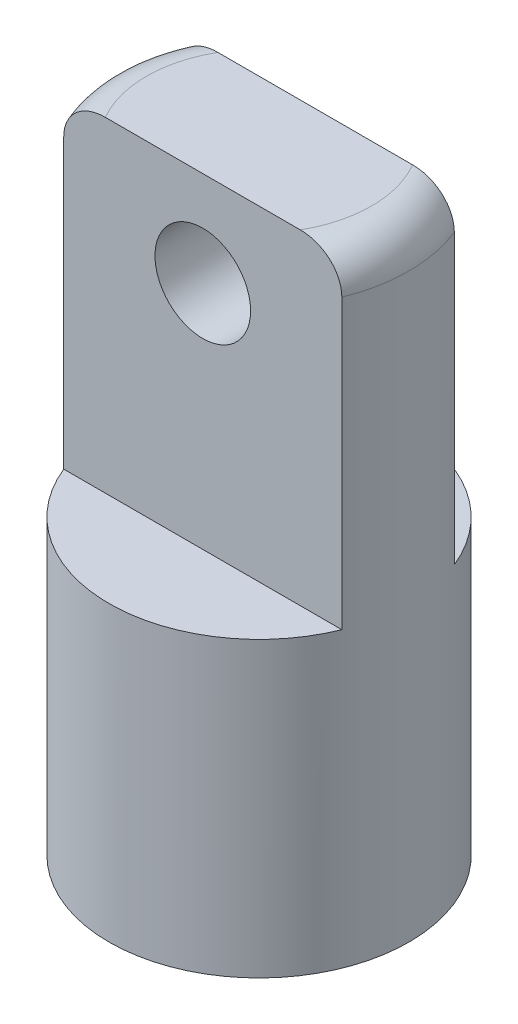
SolidWorks part; units mm, degrees
ref_plane "Front Plane" through (0, 0, 0) normal (0, 0, 1) x (1, 0, 0)
ref_plane "Top Plane" through (0, 0, 0) normal (0, 1, 0) x (1, 0, 0)
ref_plane "Right Plane" through (0, 0, 0) normal (1, 0, 0) x (0, 0, -1)
sketch "Sketch1" plane through (0, 0, 0) normal (0, 1, 0) x (1, 0, 0)
  circle A0 centre (0, 0) radius 4
  dimension "D1" = 8
extrude "Boss-Extrude1" add sketch "Sketch1" along normal blind 16.5
sketch "Sketch2" plane through (0, 16.5, 0) normal (0, 1, 0) x (1, 0, 0)
  line L0 (-4.4, 0) -> (4.4, 0) construction
  line L1 (-3.7081, 1.5) -> (3.7081, 1.5)
  line L3 (-3.7081, -1.5) -> (3.7081, -1.5)
  arc A0 (3.7081, 1.5) -> (-3.7081, 1.5) centre (0, 0) ccw
  circle A1 centre (0, 0) radius 4
  arc A2 (-3.7081, -1.5) -> (3.7081, -1.5) centre (0, 0) ccw
  dimension "D2" = 3
  dimension "D3" = 1.5
  dimension "D1" = 0
extrude "Cut-Extrude1" cut sketch "Sketch2" against normal blind 8.68
sketch "Sketch5" plane through (0, 0, 0) normal (0, -1, 0) x (1, 0, 0)
  circle A0 centre (0, 0) radius 2
  dimension "D1" = 4
extrude "Cut-Extrude3" cut sketch "Sketch5" against normal blind 7
sketch "Sketch4" plane through (0, 0, 1.5) normal (0, 0, 1) x (1, 0, 0)
  line L0 (0, -4.4) -> (0, 4.4) construction
  line L1 (3.7081, 16.5) -> (-3.7081, 16.5) construction
  line L2 (4.4, 0) -> (-4.4, 0) construction
  circle A0 centre (0, 13.965) radius 1.275
  circle A1 centre (0, 4.72) radius 1.27
  dimension "D1" = 2.55
  dimension "D3" = 2.54
  dimension "D2" = 2.535
  dimension "D4" = 4.72
extrude "Cut-Extrude2" cut sketch "Sketch4" against normal through all
fillet "Fillet1" radius 1 2 edges at (-4, 16.5, 0) (4, 16.5, 0)
